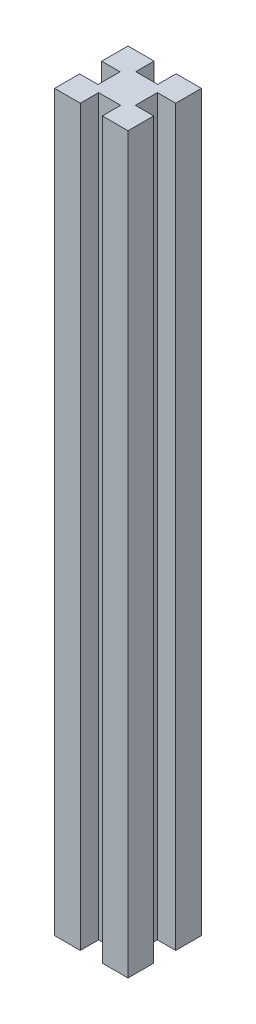
SolidWorks part; units mm, degrees
ref_plane "Plan de face" through (0, 0, 0) normal (0, 0, 1) x (1, 0, 0)
ref_plane "Plan de dessus" through (0, 0, 0) normal (0, 1, 0) x (1, 0, 0)
ref_plane "Plan de droite" through (0, 0, 0) normal (1, 0, 0) x (0, 0, -1)
sketch "Esquisse1" plane through (0, 0, 0) normal (0, 1, 0) x (1, 0, 0)
  line L1 (0, 0) -> (20, 0)
  line L2 (0, 0) -> (0, -20)
  line L3 (0, -20) -> (20, -20)
  line L4 (20, 0) -> (20, -20)
  dimension "D1" = 20
  dimension "D2" = 20
extrude "Boss.-Extru.1" add sketch "Esquisse1" along normal blind 200
sketch "Esquisse2" plane through (0, 200, 0) normal (0, 1, 0) x (1, 0, 0)
  line L0 (20, 0) -> (0, 0) construction
  line L1 (7.1122, 0) -> (13.1122, 0)
  line L2 (7.1122, 0) -> (7.1122, -5) construction
  line L3 (7.1122, -5) -> (13.1122, -5)
  line L4 (13.1122, 0) -> (13.1122, -5)
  line L5 (0, -20) -> (20, -20) construction
  line L6 (0, -7.1781) -> (5, -7.1781)
  line L7 (0, -7.1781) -> (0, -13.1781)
  line L8 (0, -13.1781) -> (5, -13.1781)
  line L9 (5, -7.1781) -> (5, -13.1781)
  line L10 (7, -20) -> (13, -20)
  line L11 (7, -20) -> (7, -15)
  line L12 (7, -15) -> (13, -15)
  line L13 (13, -20) -> (13, -15)
  line L14 (20, -20) -> (20, 0) construction
  line L15 (20, -7) -> (15, -7)
  line L16 (20, -7) -> (20, -13)
  line L17 (20, -13) -> (15, -13)
  line L18 (15, -7) -> (15, -13)
  line L19 (0, 0) -> (0, -20) construction
  line M17 (0, 0) -> (0, -20)
  line M18 (0, -20) -> (20, -20)
  line M19 (20, -20) -> (20, 0)
  line M20 (20, 0) -> (0, 0)
  dimension "D4" = 6
  dimension "D5" = 5
  dimension "D6" = 7
extrude "Enlèv. mat.-Extru.1" cut sketch "Esquisse2" against normal blind 200 contours L2 L3 L4 M20 | L9 L6 L8 M17 | L15 L18 L17 M19 | L13 L12 L11 M18
